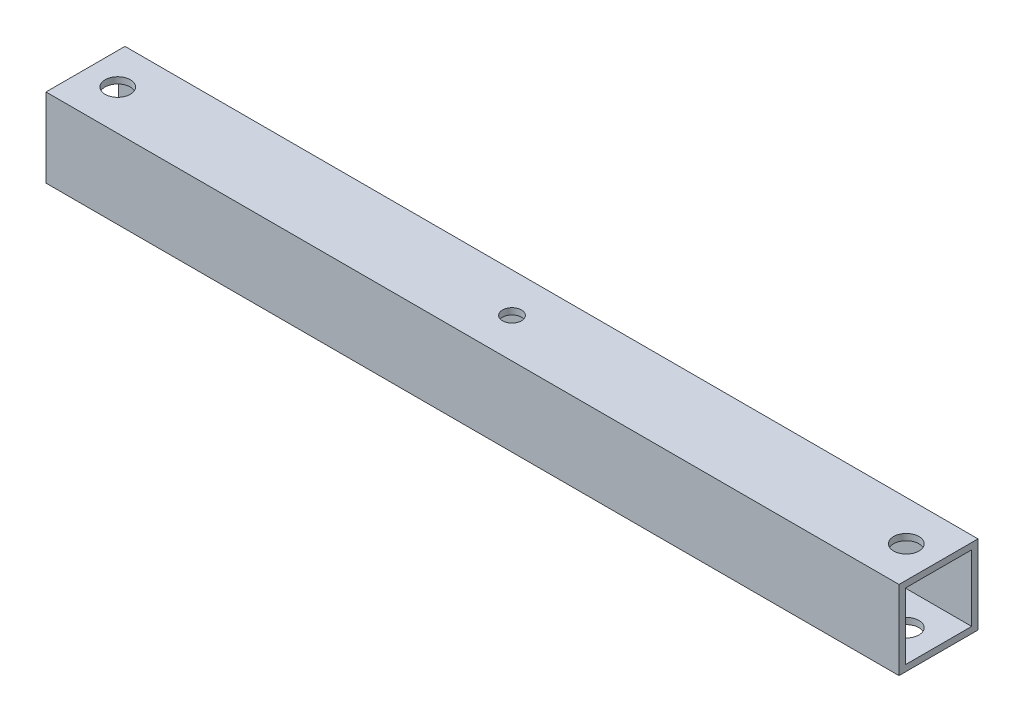
SolidWorks part; units mm, degrees
material "1060 Alloy"
ref_plane "Front Plane" through (0, 0, 0) normal (0, 0, 1) x (1, 0, 0)
ref_plane "Top Plane" through (0, 0, 0) normal (0, 1, 0) x (1, 0, 0)
ref_plane "Right Plane" through (0, 0, 0) normal (1, 0, 0) x (0, 0, -1)
sketch "Sketch1" plane through (0, 0, 0) normal (1, 0, 0) x (0, 0, -1)
  line L0 (2, 23) -> (23, 23)
  line L1 (0, 0) -> (25, 0)
  line L2 (0, 0) -> (0, 25)
  line L3 (0, 25) -> (25, 25)
  line L4 (25, 0) -> (25, 25)
  line L5 (23, 2) -> (23, 23)
  line L6 (2, 2) -> (23, 2)
  line L7 (2, 2) -> (2, 23)
  dimension "D1" = 25
  dimension "D2" = 25
  dimension "D3" = 2
extrude "Boss-Extrude1" add sketch "Sketch1" along normal blind 270
sketch "Sketch2" plane through (0, 25, 0) normal (0, 1, 0) x (1, 0, 0)
  line L0 (0, 25) -> (0, 0) construction
  line L1 (270, 0) -> (0, 0) construction
  circle A0 centre (135, 12.5) radius 3
  dimension "D1" = 6
  dimension "D2" = 135
  dimension "D3" = 12.5
extrude "Cut-Extrude1" cut sketch "Sketch2" against normal through all
sketch "Sketch3" plane through (0, 25, 0) normal (0, 1, 0) x (1, 0, 0)
  line L0 (0, 25) -> (0, 0) construction
  line L1 (270, 0) -> (0, 0) construction
  line L2 (270, 25) -> (0, 25) construction
  line L3 (270, 25) -> (270, 0) construction
  circle A0 centre (10, 12.7) radius 4
  circle A1 centre (260, 12.3) radius 4
  dimension "D1" = 8
  dimension "D4" = 8
  dimension "D2" = 10
  dimension "D3" = 12.7
  dimension "D5" = 12.7
  dimension "D6" = 10
extrude "Cut-Extrude2" cut sketch "Sketch3" against normal through all
